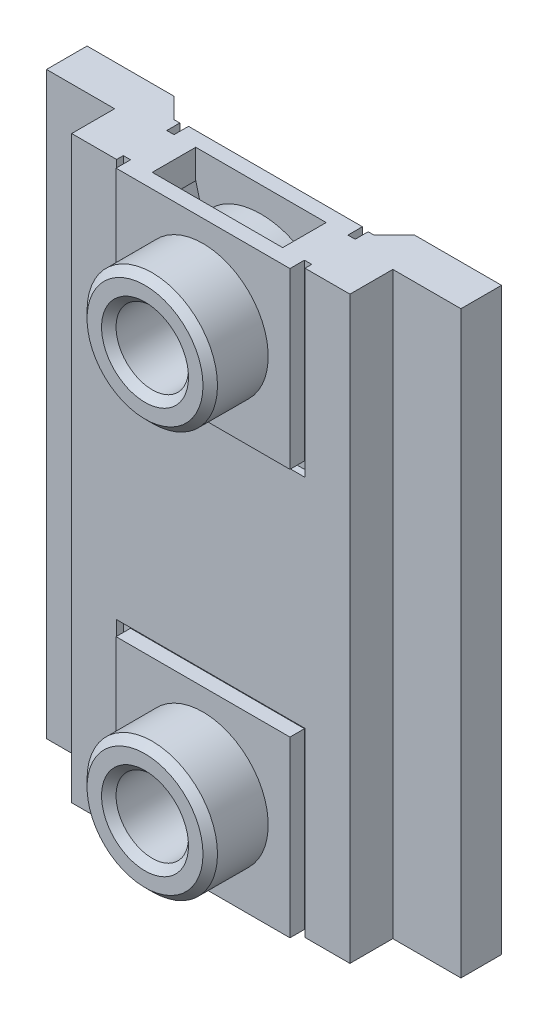
SolidWorks part; units mm, degrees
ref_plane "Ebene vorne" through (0, 0, 0) normal (0, 0, 1) x (1, 0, 0)
ref_plane "Ebene oben" through (0, 0, 0) normal (0, 1, 0) x (1, 0, 0)
ref_plane "Ebene rechts" through (0, 0, 0) normal (1, 0, 0) x (0, 0, -1)
ref_plane "Plane1" through (0, 0, 5.5) normal (0, 0, 1) x (1, 0, 0)
sketch "Sketch1" plane through (0, 0, 5.5) normal (0, 0, 1) x (1, 0, 0)
  line L0 (1.9936, -8.0431) -> (2.25, -9)
  line L1 (2.25, -9) -> (2.25, 9)
  line L2 (2.25, 9) -> (1.9936, 8.0431)
  line L3 (-1.9936, 8.0431) -> (-2.25, 9)
  line L4 (-2.25, 9) -> (-2.25, -9)
  line L5 (-2.25, -9) -> (-1.9936, -8.0431)
  spline S0 degree 3 poles (-1.9936, 8.0431) (-1.2365, 9.4901) (1.2365, 9.4901) (1.9936, 8.0431) knots 0 0 0 0 1 1 1 1
  spline S1 degree 3 poles (1.9936, -8.0431) (1.2365, -9.4901) (-1.2365, -9.4901) (-1.9936, -8.0431) knots 0 0 0 0 1 1 1 1
extrude "Boss-Extrude1" add sketch "Sketch1" against normal blind 1.5
sketch "Sketch2" plane through (0, 0, 4) normal (0, 0, -1) x (-1, 0, 0)
  line L0 (-2.25, -9.25) -> (-2.25, 10)
  line L1 (-2.25, 10) -> (2.25, 10)
  line L2 (2.25, 10) -> (2.25, -9.25)
  line L3 (2.25, -9.25) -> (-2.25, -9.25)
extrude "Boss-Extrude2" add sketch "Sketch2" along normal blind 1.15
sketch "Sketch3" plane through (0, -9.25, 0) normal (0, -1, 0) x (1, 0, 0)
  line L0 (2.25, 2.85) -> (-2.25, 2.85)
  line L1 (-2.25, 2.85) -> (-2.25, 4)
  line L2 (2.25, 4) -> (2.25, 2.85)
  spline S0 degree 3 poles (2.25, 4) (0.75, 4) (-0.75, 4) (-2.25, 4) knots 0 0 0 0 1 1 1 1
extrude "Boss-Extrude3" add sketch "Sketch3" along normal blind 0.75
sketch "Sketch4" plane through (2.25, 0, 0) normal (1, 0, 0) x (0, 0, -1)
  line L0 (-5.5, 10) -> (-2.85, 10)
  line L1 (-2.85, 10) -> (-2.85, -10)
  line L2 (-2.85, -10) -> (-5.5, -10)
  line L3 (-5.5, -10) -> (-5.5, 10)
extrude "Boss-Extrude4" add sketch "Sketch4" along normal blind 4.9
sketch "Sketch5" plane through (-2.25, 0, 0) normal (-1, 0, 0) x (0, 0, 1)
  line L0 (5.5, -10) -> (2.85, -10)
  line L1 (2.85, -10) -> (2.85, 10)
  line L2 (2.85, 10) -> (5.5, 10)
  line L3 (5.5, 10) -> (5.5, -10)
extrude "Boss-Extrude5" add sketch "Sketch5" along normal blind 4.9
sketch "Sketch6" plane through (0, 0, 5.5) normal (0, 0, 1) x (1, 0, 0)
  line L0 (7.15, 10) -> (7.15, -10)
  line L1 (7.15, -10) -> (-7.15, -10)
  line L2 (-7.15, -10) -> (-7.15, 10)
  line L3 (-7.15, 10) -> (7.15, 10)
extrude "Boss-Extrude6" add sketch "Sketch6" along normal blind 0.23
sketch "Sketch7" plane through (0, -10, 0) normal (0, -1, 0) x (1, 0, 0)
  line L0 (-3.45, 2.85) -> (3.45, 2.85)
  line L1 (3.45, 2.85) -> (3.45, 3.55)
  line L2 (3.45, 3.55) -> (-3.45, 3.55)
  line L3 (-3.45, 3.55) -> (-3.45, 2.85)
extrude "Cut-Extrude1" cut sketch "Sketch7" against normal through all
ref_plane "Plane2" through (0, -10, 0) normal (0, -1, 0) x (1, 0, 0)
ref_plane "Plane3" through (0, -3.75, 0) normal (0, 1, 0) x (1, 0, 0)
sketch "Sketch9" plane through (0, -3.75, 0) normal (0, 1, 0) x (1, 0, 0)
  line L0 (3.25, -4) -> (3.25, -3.55)
  line L1 (3.25, -3.55) -> (-3.25, -3.55)
  line L2 (-3.25, -3.55) -> (-3.25, -4)
  spline S0 degree 3 poles (3.25, -4) (1.0833, -4) (-1.0833, -4) (-3.25, -4) knots 0 0 0 0 1 1 1 1
extrude "Cut-Extrude2" cut sketch "Sketch9" against normal up to surface up to plane "Plane2"
ref_plane "Plane4" through (0, 10, 0) normal (0, 1, 0) x (1, 0, 0)
ref_plane "Plane5" through (0, 3.75, 0) normal (0, -1, 0) x (1, 0, 0)
sketch "Sketch11" plane through (0, 3.75, 0) normal (0, -1, 0) x (1, 0, 0)
  line L0 (-3.25, 4) -> (-3.25, 3.55)
  line L1 (-3.25, 3.55) -> (3.25, 3.55)
  line L2 (3.25, 3.55) -> (3.25, 4)
  spline S0 degree 3 poles (-3.25, 4) (-1.0833, 4) (1.0833, 4) (3.25, 4) knots 0 0 0 0 1 1 1 1
extrude "Cut-Extrude3" cut sketch "Sketch11" against normal up to surface up to plane "Plane4"
sketch "Sketch12" plane through (0, 10, 0) normal (0, 1, 0) x (-1, 0, 0)
  line L0 (-3.25, 5.5) -> (3.25, 5.5)
  line L1 (3.25, 5.5) -> (3.25, 5.73)
  line L2 (3.25, 5.73) -> (-3.25, 5.73)
  line L3 (-3.25, 5.73) -> (-3.25, 5.5)
extrude "Cut-Extrude4" cut sketch "Sketch12" against normal blind 6.25
sketch "Sketch13" plane through (0, -10, 0) normal (0, -1, 0) x (1, 0, 0)
  line L0 (-3.25, 5.5) -> (3.25, 5.5)
  line L1 (3.25, 5.5) -> (3.25, 5.73)
  line L2 (3.25, 5.73) -> (-3.25, 5.73)
  line L3 (-3.25, 5.73) -> (-3.25, 5.5)
extrude "Cut-Extrude5" cut sketch "Sketch13" against normal blind 6.25
sketch "Sketch14" plane through (0, 10, 0) normal (0, 1, 0) x (-1, 0, 0)
  line L0 (4.8, 5.73) -> (4.8, 4.25)
  line L1 (4.8, 4.25) -> (7.15, 4.25)
  line L2 (7.15, 4.25) -> (7.15, 5.73)
  line L3 (7.15, 5.73) -> (4.8, 5.73)
extrude "Cut-Extrude6" cut sketch "Sketch14" against normal through all
sketch "Sketch15" plane through (0, 10, 0) normal (0, 1, 0) x (-1, 0, 0)
  line L0 (-7.15, 5.73) -> (-7.15, 4.25)
  line L1 (-7.15, 4.25) -> (-4.8, 4.25)
  line L2 (-4.8, 4.25) -> (-4.8, 5.73)
  line L3 (-4.8, 5.73) -> (-7.15, 5.73)
extrude "Cut-Extrude7" cut sketch "Sketch15" against normal through all
sketch "Sketch16" plane through (0, 0, 4) normal (0, 0, -1) x (-1, 0, 0)
  line L0 (3, 4) -> (-3, 4)
  line L1 (-3, 4) -> (-3, 10)
  line L2 (-3, 10) -> (3, 10)
  line L3 (3, 10) -> (3, 4)
extrude "Boss-Extrude7" add sketch "Sketch16" along normal blind 0.5
sketch "Sketch17" plane through (0, 0, 5.5) normal (0, 0, 1) x (1, 0, 0)
  line L0 (-3, 4) -> (-3, 10)
  line L1 (-3, 10) -> (3, 10)
  line L2 (3, 10) -> (3, 4)
  line L3 (3, 4) -> (-3, 4)
extrude "Boss-Extrude8" add sketch "Sketch17" along normal blind 0.5
sketch "Sketch18" plane through (0, 0, 4) normal (0, 0, -1) x (-1, 0, 0)
  line L0 (3, -10) -> (-3, -10)
  line L1 (-3, -10) -> (-3, -4)
  line L2 (-3, -4) -> (3, -4)
  line L3 (3, -4) -> (3, -10)
extrude "Boss-Extrude9" add sketch "Sketch18" along normal blind 0.5
sketch "Sketch19" plane through (0, 0, 5.5) normal (0, 0, 1) x (1, 0, 0)
  line L0 (-3, -10) -> (-3, -4)
  line L1 (-3, -4) -> (3, -4)
  line L2 (3, -4) -> (3, -10)
  line L3 (3, -10) -> (-3, -10)
extrude "Boss-Extrude10" add sketch "Sketch19" along normal blind 0.5
draft "Draft1" type of draft neutral plane draft angle 45 faces to draft 2 face at (-3.45, 0, 3.2) face at (3.45, 0, 3.2) neutral plane through (3.45, 10, 3.55) neutral plane normal (0, 0, -1) parameters "D1"=45
ref_plane "Plane6" through (0, -7, 0) normal (0, -1, 0) x (1, 0, 0)
sketch "Sketch20" plane through (0, -7, 0) normal (0, -1, 0) x (1, 0, 0)
  line L0 (2.25, 8) -> (0, 8)
  line L1 (0, 8) -> (0, 6)
  line L2 (0, 6) -> (2.25, 6)
  line L3 (2.25, 6) -> (2.25, 8)
  line L4 (0, 8) -> (0, 5.9975) construction
revolve "Revolve1" add sketch "Sketch20" angle 360 about L4
ref_plane "Plane7" through (0, 7, 0) normal (0, -1, 0) x (1, 0, 0)
sketch "Sketch21" plane through (0, 7, 0) normal (0, -1, 0) x (1, 0, 0)
  line L0 (2.25, 8) -> (0, 8)
  line L1 (0, 8) -> (0, 6)
  line L2 (0, 6) -> (2.25, 6)
  line L3 (2.25, 6) -> (2.25, 8)
  line L4 (0, 8) -> (0, 5.9975) construction
revolve "Revolve2" add sketch "Sketch21" angle 360 about L4
hole_wizard "Ø2.5 (2.5) Diameter Hole1" positions "Sketch23" profile "Sketch22" hole size "Ø2.5" standard "ANSI Metric"
sketch "Sketch23" plane through (0, 0, 3.5) normal (0, 0, -1) x (-1, 0, 0)
  point P0 (0, -7)
sketch "Sketch22" plane through (0, -7, 3.5) normal (1, 0, 0) x (0, 1, 0)
  line L0 (0, 0) -> (0, 4.5)
  line L1 (0, 4.5) -> (1.25, 4.5)
  line L2 (1.25, 4.5) -> (1.25, 0)
  line L5 (1.25, 0) -> (0, 0)
  line L11 (0, -6.35) -> (0, 107.95) construction
  dimension "Thru Hole Dia." = 2.5
  dimension "Thru Hole Depth" = 4.5
hole_wizard "Ø2.5 (2.5) Diameter Hole2" positions "Sketch25" profile "Sketch24" hole size "Ø2.5" standard "ANSI Metric"
sketch "Sketch25" plane through (0, 0, 8) normal (0, 0, 1) x (1, 0, 0)
  point P0 (0, 7)
sketch "Sketch24" plane through (0, 7, 8) normal (1, 0, 0) x (0, -1, 0)
  line L0 (0, 0) -> (0, 5.15)
  line L1 (0, 5.15) -> (1.25, 5.15)
  line L2 (1.25, 5.15) -> (1.25, 0)
  line L5 (1.25, 0) -> (0, 0)
  line L11 (0, -6.35) -> (0, 107.95) construction
  dimension "Thru Hole Dia." = 2.5
  dimension "Thru Hole Depth" = 5.15
chamfer "Chamfer1" distance 0.25 angle 45 6 edges at (-1.25, -7, 8) (-2.25, -7, 8) (-2.25, 7, 8) (-1.25, -7, 3.5) (1.25, 7, 3.5) (1.25, 7, 8)
